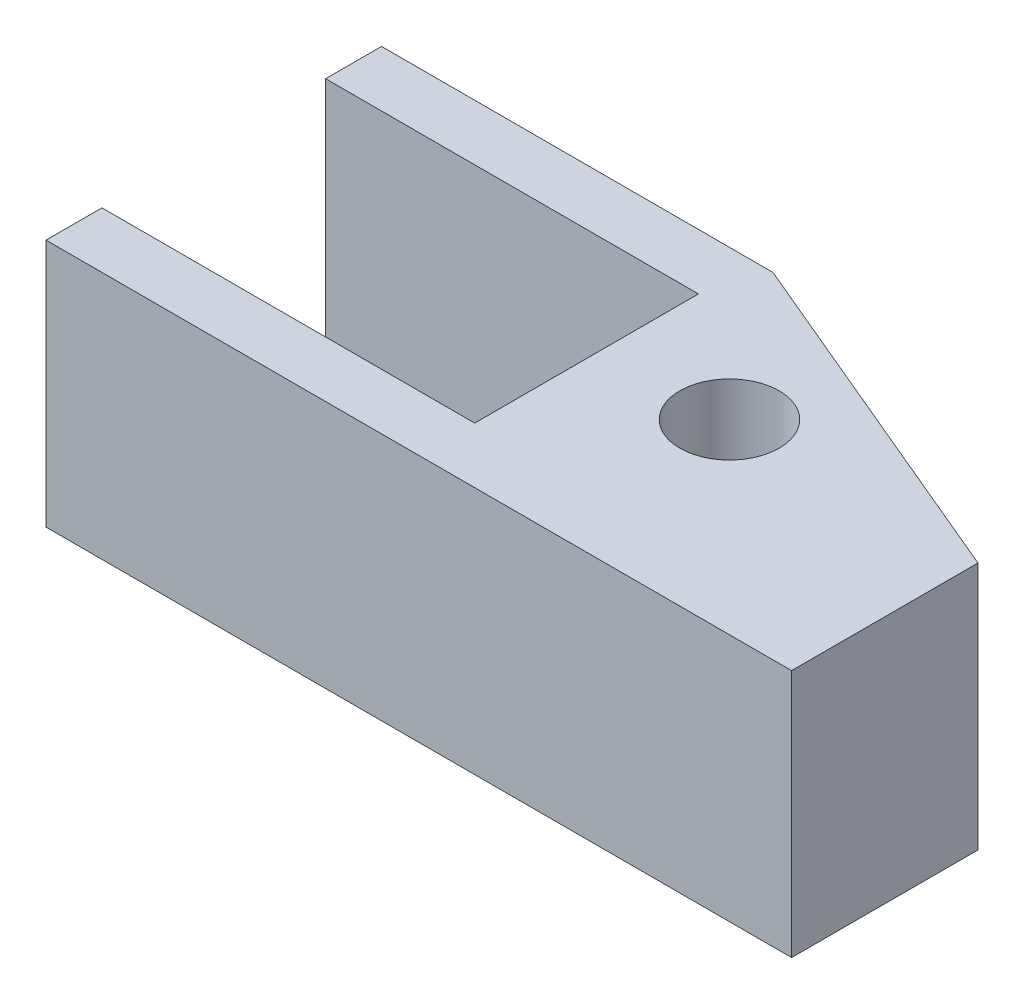
SolidWorks part; units mm, degrees
material "ABS"
ref_plane "前视基准面" through (0, 0, 0) normal (0, 0, 1) x (1, 0, 0)
ref_plane "上视基准面" through (0, 0, 0) normal (0, 1, 0) x (1, 0, 0)
ref_plane "右视基准面" through (0, 0, 0) normal (1, 0, 0) x (0, 0, -1)
sketch "草图1" plane through (0, 0, 0) normal (0, 1, 0) x (1, 0, 0)
  line L0 (-40.8824, 0) -> (72.6471, 0) construction
  line L1 (-30, 13.5) -> (1.5, 13.5)
  line L2 (-30, 13.5) -> (-30, 9)
  line L3 (-30, -13.5) -> (30, -13.5)
  line L4 (30, 1.5) -> (30, -13.5)
  line L6 (-30, -9) -> (-30, -13.5)
  line L7 (1.5, 13.5) -> (30, 1.5)
  line L8 (0, -9) -> (-30, -9)
  line L9 (0, -9) -> (0, 9)
  line L10 (0, 9) -> (-30, 9)
  line L12 (0, -9) -> (-30, 9) construction
  line L13 (0, 9) -> (-30, -9) construction
  circle A0 centre (10, 1.5) radius 4
  point P0 (0, 0)
  point P4 (-15, 0)
  point P16 (0, 0)
  dimension "D4" = 8
  dimension "D1" = 27
  dimension "D2" = 60
  dimension "D3" = 20
  dimension "D5" = 15
  dimension "D6" = 31.5
  dimension "D7" = 30
  dimension "D8" = 18
  dimension "D9" = 15
extrude "凸台-拉伸1" add sketch "草图1" along normal blind 20
